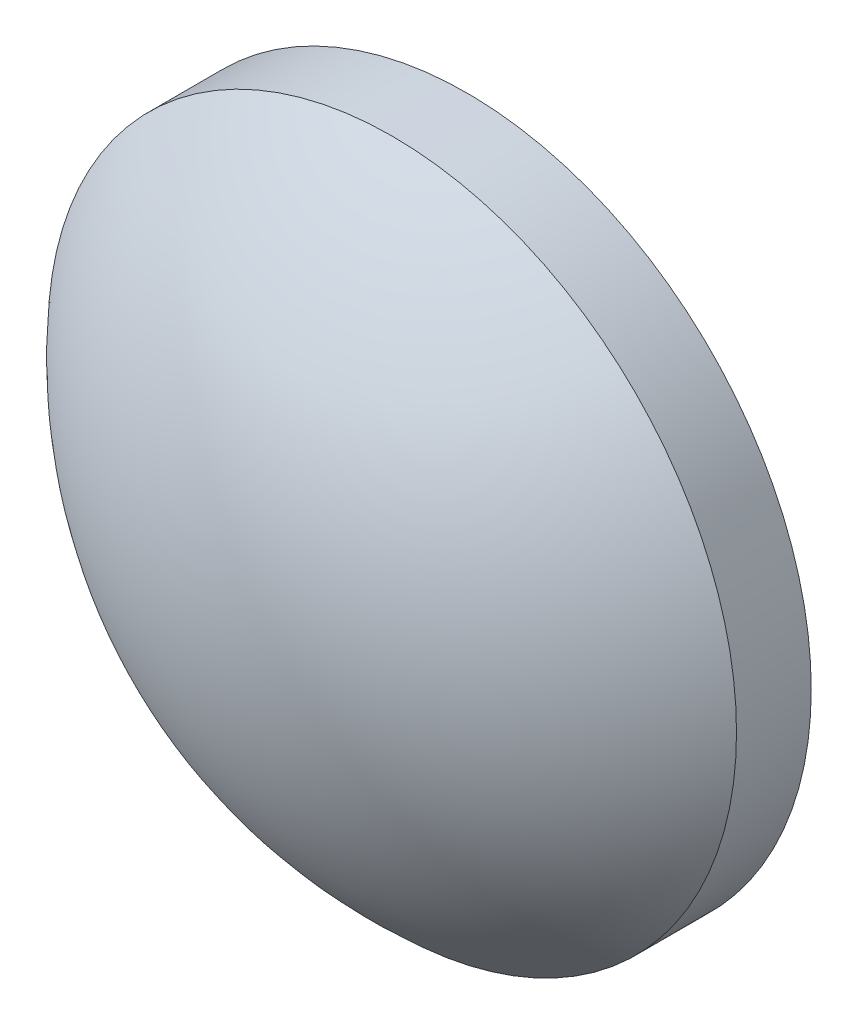
SolidWorks part; units mm, degrees
material "Настроенная пользователем пластмасса"
ref_plane "Спереди" through (0, 0, 0) normal (0, 0, 1) x (1, 0, 0)
ref_plane "Сверху" through (0, 0, 0) normal (0, 1, 0) x (1, 0, 0)
ref_plane "Справа" through (0, 0, 0) normal (1, 0, 0) x (0, 0, -1)
sketch "Эскиз1" plane through (0, 0, 0) normal (1, 0, 0) x (0, 0, -1)
  line L2 (-1.0308, 0) -> (0.9725, 0)
  line L4 (0.3217, -0.0015) -> (0.3217, 0)
  line L5 (-1.9221, 0) -> (2.9692, 0) construction
  line L7 (0.9725, 0) -> (0.9725, 2.9985)
  line L8 (0.9725, 2.9985) -> (0.3217, 2.9985)
  arc A0 (0.3217, 2.9985) -> (-1.0308, 0) centre (2.9692, 0) ccw
revolve "Повернуть6" add sketch "Эскиз1" angle 360 about L5
